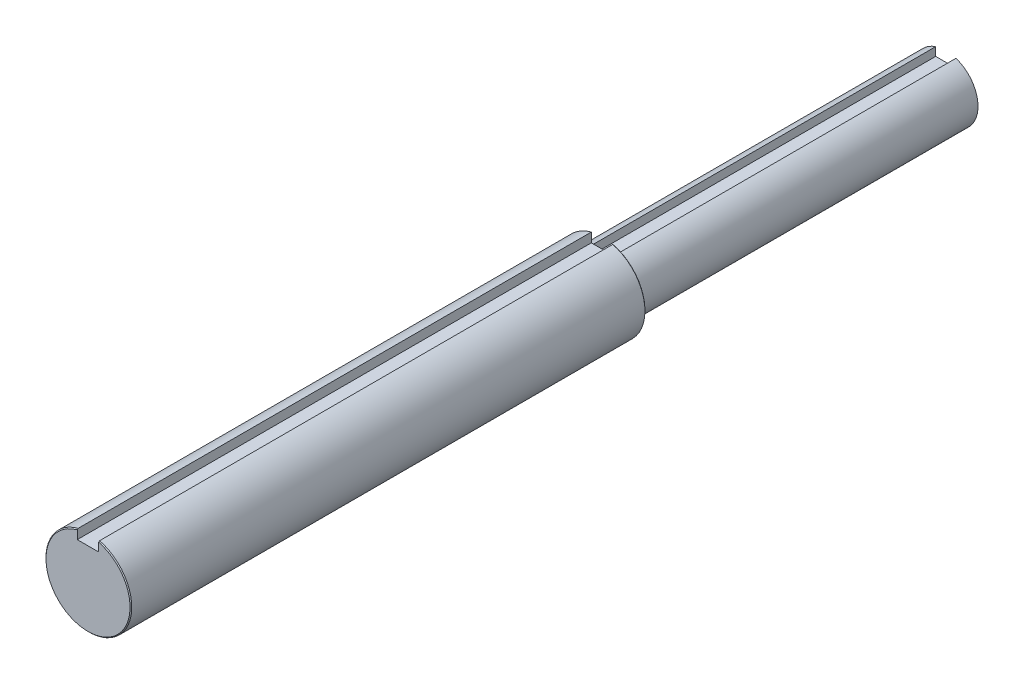
SolidWorks part; units mm, degrees
ref_plane "Front Plane" through (0, 0, 0) normal (0, 0, 1) x (1, 0, 0)
ref_plane "Top Plane" through (0, 0, 0) normal (0, 1, 0) x (1, 0, 0)
ref_plane "Right Plane" through (0, 0, 0) normal (1, 0, 0) x (0, 0, -1)
sketch "Sketch1" plane through (0, 0, 0) normal (1, 0, 0) x (0, 0, -1)
  line L0 (0, 0) -> (0, 12.7) construction
  line L1 (-304.8, 12.7) -> (304.8, 12.7)
  line L2 (-304.8, 12.7) -> (-304.8, -12.7)
  line L3 (-304.8, -12.7) -> (304.8, -12.7)
  line L4 (304.8, 12.7) -> (304.8, -12.7)
  line L5 (-304.8, 12.7) -> (304.8, -12.7) construction
  line L6 (-304.8, -12.7) -> (304.8, 12.7) construction
  line L7 (0, 0) -> (0, -12.7) construction
  point P0 (0, 0)
  point P8 (-275.59, 12.7)
  point P10 (275.59, 12.7)
  point P11 (-265.8533, -12.7)
  point P12 (271.0713, -12.7)
  dimension "Diameter" = 25.4
  dimension "Length" = 609.6
  dimension "D1" = 29.21
  dimension "D2" = 29.21
  dimension "D3" = 38.9467
  dimension "D4" = 33.7287
  dimension "Keyway Length" = 609.6
sketch "Sketch2" plane through (0, 0, 0) normal (0, 0, 1) x (1, 0, 0)
  line L0 (0, 0) -> (0, 12.7) construction
  line L2 (3.175, 9.525) -> (-3.175, 9.525)
  line L3 (3.175, 9.525) -> (3.175, 12.7)
  line L4 (3.175, 12.7) -> (-3.175, 12.7)
  line L5 (-3.175, 9.525) -> (-3.175, 12.7)
  line L6 (3.175, 9.525) -> (-3.175, 12.7) construction
  line L7 (3.175, 12.7) -> (-3.175, 9.525) construction
  circle A0 centre (0, 0) radius 12.7
  point P3 (0, 11.1125)
  point P10 (0, -12.7)
  dimension "D1" = 22.225
  dimension "Keyway Width" = 6.35
  dimension "Keyway Depth" = 3.175
sketch "Sketch3" plane through (0, 0, 0) normal (0, 0, 1) x (1, 0, 0)
  line L1 (-3.175, 9.525) -> (-3.175, 12.7) construction
  line L2 (3.175, 9.525) -> (-3.175, 9.525) construction
  line L3 (3.175, 9.525) -> (3.175, 12.7) construction
  line L5 (-3.175, 9.525) -> (-3.175, 12.2967)
  line L6 (3.175, 9.525) -> (-3.175, 9.525)
  line L7 (3.175, 9.525) -> (3.175, 12.2967)
  arc A1 (-3.175, 12.2967) -> (3.175, 12.2967) centre (0, 0) ccw
  circle A2 centre (0, 0) radius 12.7 construction
extrude "Boss-Extrude1" add sketch "Sketch3" along normal up to vertex (304.8 mm away) and the other way up to vertex (304.8 mm away) up to point (0, 12.7, 304.8) other way up to point (0, 12.7, -304.8)
chamfer "Chamfer1" distance 0.254 angle 45 2 edges at (0, -12.7, 304.8) (0, -12.7, -304.8)
ref_plane "Plane1" through (0, 0, 152.4) normal (0, 0, 1) x (1, 0, 0)
sketch "Sketch5" plane through (0, 0, 152.4) normal (0, 0, 1) x (1, 0, 0)
  circle A0 centre (0, 0) radius 9.525
  circle A1 centre (0, 0) radius 12.7
  dimension "D1" = 19.05
  dimension "D2" = 25.4
extrude "Cut-Extrude1" cut sketch "Sketch5" against normal through all
sketch "Sketch6" plane through (0, 0, 152.4) normal (0, 0, 1) x (1, 0, 0)
  line L0 (3.175, 9.525) -> (-3.175, 9.525) construction
  line L1 (-3, 12.525) -> (3, 12.525)
  line L2 (-3, 12.525) -> (-3, 6.525)
  line L3 (-3, 6.525) -> (3, 6.525)
  line L4 (3, 12.525) -> (3, 6.525)
  line L5 (-3, 12.525) -> (3, 6.525) construction
  line L6 (-3, 6.525) -> (3, 12.525) construction
  point P0 (0, 9.525)
  dimension "D1" = 6
  dimension "D2" = 6
extrude "Cut-Extrude2" cut sketch "Sketch6" against normal through all
chamfer "Chamfer2" distance 0.2 angle 45 8 edges at (-3, 7.7826, 152.4) (0, 6.525, 152.4) (3, 7.7826, 152.4) (0, -9.525, 152.4) (0, 9.525, 152.4) (3.175, 10.9109, 152.4) (-3.175, 10.9109, 152.4) (0, -12.7, 152.4)
ref_plane "Plane2" through (0, 0, 50.8) normal (0, 0, 1) x (1, 0, 0)
sketch "Sketch7" plane through (0, 0, 50.8) normal (0, 0, 1) x (1, 0, 0)
  circle A0 centre (0, 0) radius 63.5
  dimension "D1" = 127
extrude "Cut-Extrude3" cut sketch "Sketch7" against normal through all
equation "\"D2@Sketch1\"=1.15*\"Diameter@Sketch1\""
equation "\"D1@Sketch1\"=\"D2@Sketch1\""
equation "\"D3@Sketch1\"=\"D2@Sketch1\"*4/3"
equation "\"D4@Sketch1\"=\"D2@Sketch1\"/(tan(.5236*180/pi)*2)*4/3"
equation "\"D1@Chamfer1\"=\"Diameter@Sketch1\"*.01"
